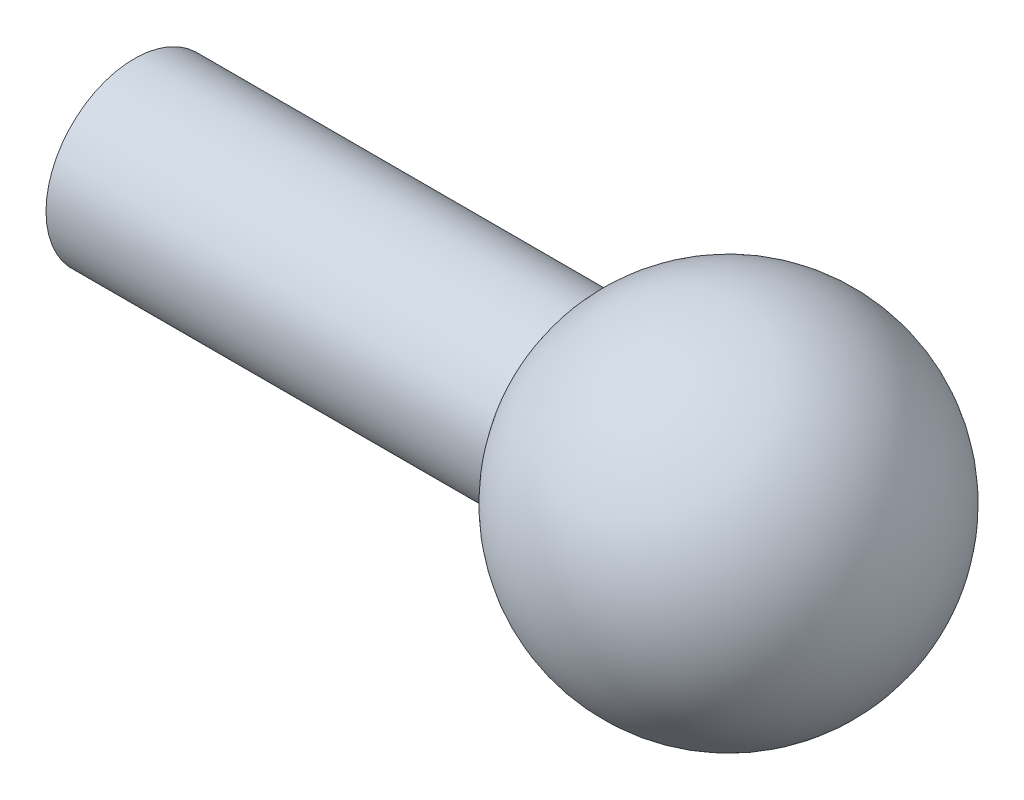
SolidWorks part; units mm, degrees
ref_plane "Front Plane" through (0, 0, 0) normal (0, 0, 1) x (1, 0, 0)
ref_plane "Top Plane" through (0, 0, 0) normal (0, 1, 0) x (1, 0, 0)
ref_plane "Right Plane" through (0, 0, 0) normal (1, 0, 0) x (0, 0, -1)
sketch "Sketch1" plane through (0, 0, 0) normal (0, 1, 0) x (1, 0, 0)
  line L0 (-6.35, 0) -> (15.8294, 0)
  line L1 (6.35, 2.54) -> (-6.35, 2.54)
  line L4 (-6.35, 2.54) -> (-6.35, 0)
  line L5 (6.35, 2.54) -> (0, 0) construction
  line L6 (0, 0) -> (-6.35, 2.54) construction
  arc A1 (6.35, 2.54) -> (15.8294, 0) centre (10.7494, 0) cw
  point P0 (0, 0)
  dimension "D3" = 5.08
  dimension "D1" = 2.54
  dimension "D2" = 12.7
  dimension "D4" = 6.35
revolve "Revolve1" add sketch "Sketch1" angle 360 about L0
